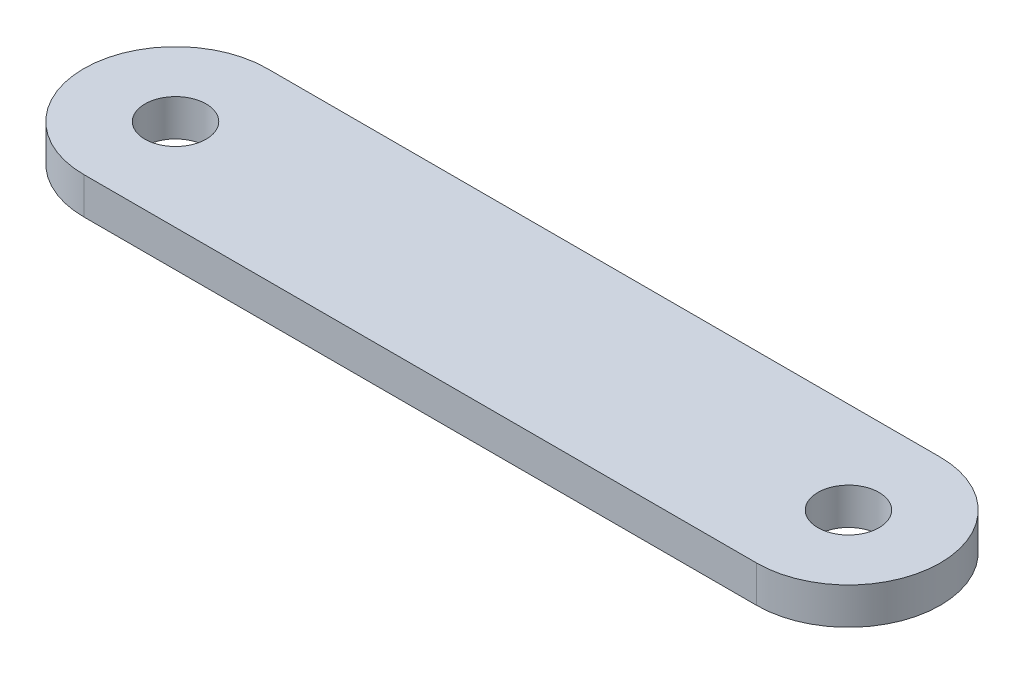
SolidWorks part; units mm, degrees
ref_plane "Front Plane" through (0, 0, 0) normal (0, 0, 1) x (1, 0, 0)
ref_plane "Top Plane" through (0, 0, 0) normal (0, 1, 0) x (1, 0, 0)
ref_plane "Right Plane" through (0, 0, 0) normal (1, 0, 0) x (0, 0, -1)
sketch "Sketch2" plane through (0, 0, 0) normal (0, 1, 0) x (1, 0, 0)
  line L1 (-45, 15) -> (65, 15)
  line L3 (-45, -15) -> (65, -15)
  arc A0 (-45, 15) -> (-45, -15) centre (-45, 0) ccw
  arc A1 (65, -15) -> (65, 15) centre (65, 0) ccw
  circle A2 centre (-45, 0) radius 5
  circle A3 centre (65, 0) radius 5
  point P0 (0, 0)
  point P7 (0, 0)
extrude "Boss-Extrude1" add sketch "Sketch2" along normal blind 6
